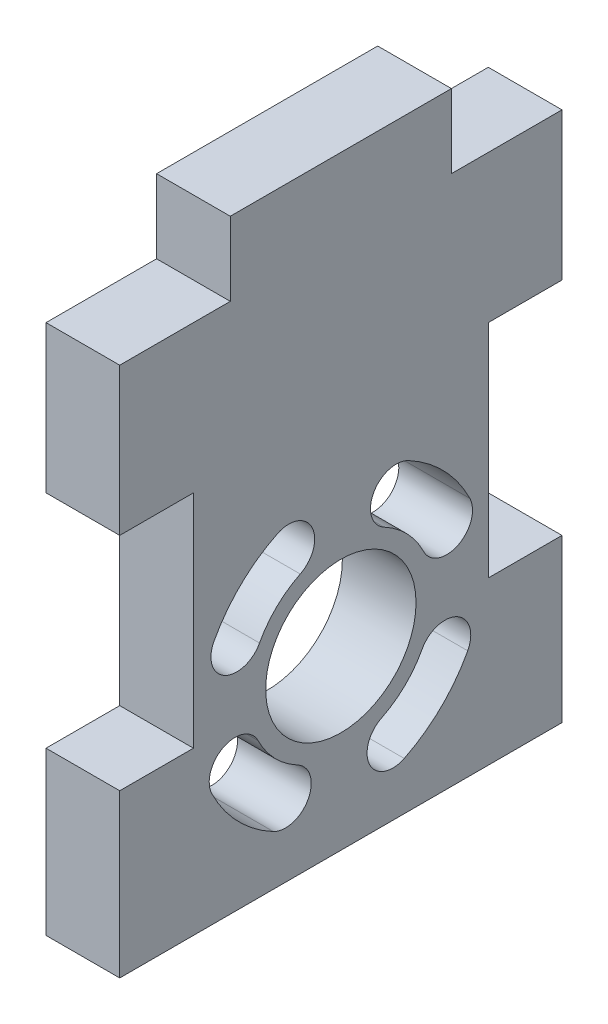
SolidWorks part; units mm, degrees
ref_plane "前视基准面" through (0, 0, 0) normal (0, 0, 1) x (1, 0, 0)
ref_plane "上视基准面" through (0, 0, 0) normal (0, 1, 0) x (1, 0, 0)
ref_plane "右视基准面" through (0, 0, 0) normal (1, 0, 0) x (0, 0, -1)
sketch "草图1" plane through (0, 0, 0) normal (1, 0, 0) x (0, 0, -1)
  line L0 (-22.5, 36) -> (-30, 36)
  line L1 (0, 0) -> (-30, 0)
  line L2 (0, 0) -> (0, 11)
  line L3 (0, 36) -> (-7.5, 36)
  line L4 (-30, 0) -> (-30, 11)
  line L5 (-30, 26) -> (-25, 26)
  line L6 (0, 26) -> (0, 36)
  line L7 (-30, 11) -> (-25, 11)
  line L8 (-25, 26) -> (-25, 11)
  line L9 (0, 26) -> (-5, 26)
  line L10 (-15, 45.8347) -> (-15, -11.3289) construction
  line L11 (0, 11) -> (-5, 11)
  line L12 (-5, 26) -> (-5, 11)
  line L13 (-30, 26) -> (-30, 36)
  line L14 (-22.5, 36) -> (-22.5, 41)
  line L15 (-22.5, 41) -> (-7.5, 41)
  line L16 (-7.5, 36) -> (-7.5, 41)
  line L17 (-38.0771, 12) -> (15.2357, 12) construction
  arc A0 (-11.2405, 19.0616) -> (-7.8195, 15.527) centre (-15, 12) cw construction
  circle A1 centre (-15, 12) radius 5.1
  arc A2 (-22.0616, 15.7595) -> (-18.527, 19.1805) centre (-15, 12) cw construction
  arc A3 (-19.2986, 20.7513) -> (-23.6063, 16.5819) centre (-15, 12) ccw
  arc A4 (-17.7555, 17.6098) -> (-20.5169, 14.9371) centre (-15, 12) ccw
  arc A5 (-17.7555, 17.6098) -> (-19.2986, 20.7513) centre (-18.527, 19.1805) ccw
  arc A6 (-23.6063, 16.5819) -> (-20.5169, 14.9371) centre (-22.0616, 15.7595) ccw
  arc A7 (-6.2487, 16.2986) -> (-10.4181, 20.6063) centre (-15, 12) ccw
  arc A8 (-9.3902, 14.7555) -> (-12.0629, 17.5169) centre (-15, 12) ccw
  arc A9 (-9.3902, 14.7555) -> (-6.2487, 16.2986) centre (-7.8195, 15.527) ccw
  arc A10 (-10.4181, 20.6063) -> (-12.0629, 17.5169) centre (-11.2405, 19.0616) ccw
  arc A11 (-7.9384, 8.2405) -> (-11.473, 4.8195) centre (-15, 12) cw construction
  arc A12 (-10.7014, 3.2487) -> (-6.3937, 7.4181) centre (-15, 12) ccw
  arc A13 (-12.2445, 6.3902) -> (-9.4831, 9.0629) centre (-15, 12) ccw
  arc A14 (-12.2445, 6.3902) -> (-10.7014, 3.2487) centre (-11.473, 4.8195) ccw
  arc A15 (-6.3937, 7.4181) -> (-9.4831, 9.0629) centre (-7.9384, 8.2405) ccw
  arc A16 (-18.7595, 4.9384) -> (-22.1805, 8.473) centre (-15, 12) cw construction
  arc A17 (-23.7513, 7.7014) -> (-19.5819, 3.3937) centre (-15, 12) ccw
  arc A18 (-20.6098, 9.2445) -> (-17.9371, 6.4831) centre (-15, 12) ccw
  arc A19 (-20.6098, 9.2445) -> (-23.7513, 7.7014) centre (-22.1805, 8.473) ccw
  arc A20 (-19.5819, 3.3937) -> (-17.9371, 6.4831) centre (-18.7595, 4.9384) ccw
  point P27 (-20.5638, 17.7484)
  point P35 (-9.2516, 17.5638)
  point P42 (-9.4362, 6.2516)
  point P49 (-20.7484, 6.4362)
  point P53 (-53.045, 23.518)
  point P55 (-15, 12)
  dimension "D12" = 10.2
  dimension "D15" = 1.75
  dimension "D1" = 30
  dimension "D2" = 36
  dimension "D3" = 5
  dimension "D4" = 5
  dimension "D5" = 5
  dimension "D6" = 15
  dimension "D7" = 15
  dimension "D8" = 15
  dimension "D9" = 10
  dimension "D10" = 10
  dimension "D11" = 7.5
  dimension "D13" = 8
  dimension "D14" = 4.919
  dimension "D16" = 7.5
  dimension "D17" = 29
  dimension "D18" = 0
  dimension "D19" = 0
  dimension "D20" = 4
extrude "凸台-拉伸1" add sketch "草图1" along normal blind 5
